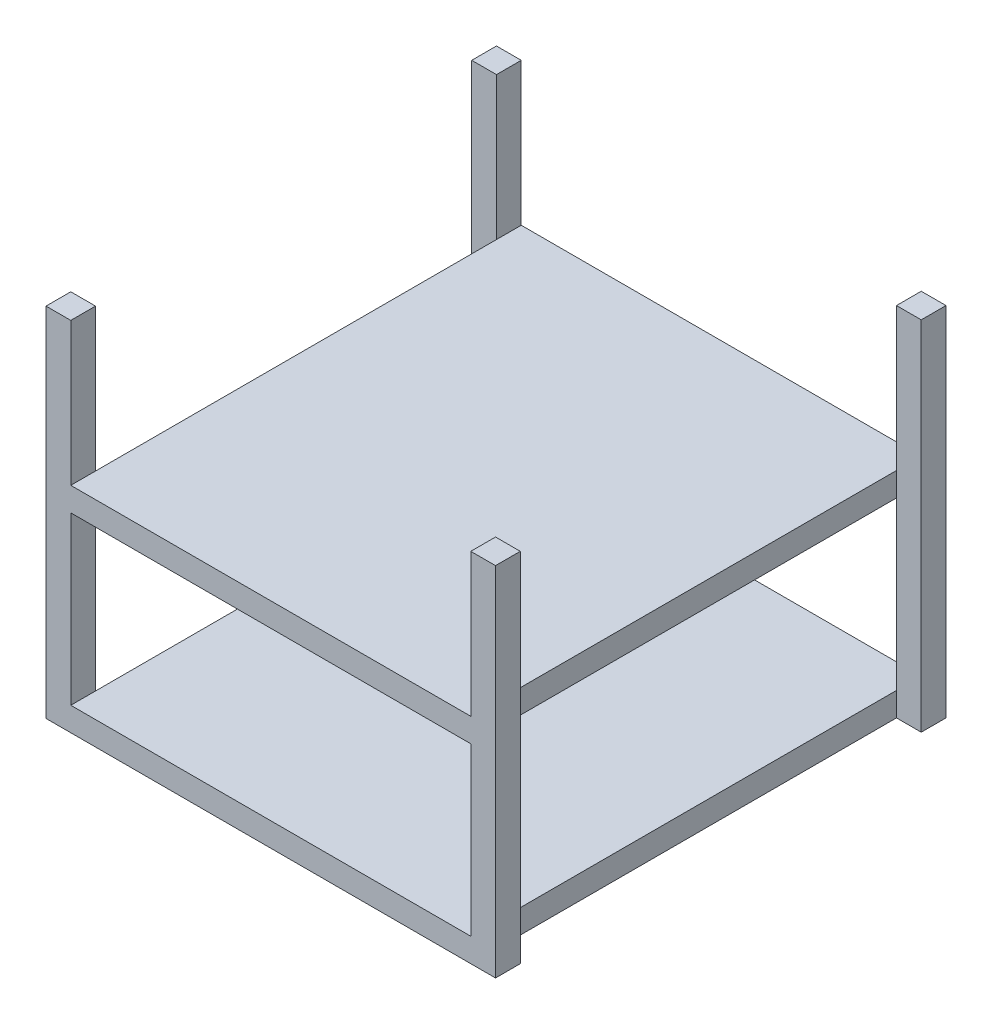
SolidWorks part; units mm, degrees
ref_plane "Front Plane" through (0, 0, 0) normal (0, 0, 1) x (1, 0, 0)
ref_plane "Top Plane" through (0, 0, 0) normal (0, 1, 0) x (1, 0, 0)
ref_plane "Right Plane" through (0, 0, 0) normal (1, 0, 0) x (0, 0, -1)
sketch "Sketch1" plane through (0, 0, 0) normal (0, 1, 0) x (1, 0, 0)
  line L0 (0, 120.142) -> (0, -120.142)
  line L1 (-127, -127) -> (127, -127)
  line L2 (-127, -127) -> (-127, 127)
  line L3 (-127, 127) -> (127, 127)
  line L4 (127, -127) -> (127, 127)
  line L5 (-127, -127) -> (127, 127) construction
  line L6 (-127, 127) -> (127, -127) construction
  line L7 (106.68, 120.142) -> (-106.68, 120.142)
  line L8 (106.68, 120.142) -> (106.68, -120.142)
  line L9 (106.68, -120.142) -> (-106.68, -120.142)
  line L10 (-106.68, 120.142) -> (-106.68, -120.142)
  line L11 (-106.68, 120.142) -> (-119.888, 120.142)
  line L12 (-106.68, 120.142) -> (-106.68, 106.934)
  line L13 (-106.68, 106.934) -> (-119.888, 106.934)
  line L14 (-119.888, 120.142) -> (-119.888, 106.934)
  line L15 (106.68, 0) -> (-106.68, 0)
  line L16 (106.68, 106.934) -> (119.888, 106.934)
  line L17 (119.888, 120.142) -> (119.888, 106.934)
  line L18 (106.68, 120.142) -> (119.888, 120.142)
  line L19 (106.68, 120.142) -> (106.68, 106.934)
  line L20 (106.68, -120.142) -> (119.888, -120.142)
  line L21 (119.888, -120.142) -> (119.888, -106.934)
  line L22 (106.68, -106.934) -> (119.888, -106.934)
  line L23 (106.68, -120.142) -> (106.68, -106.934)
  line L24 (-106.68, -106.934) -> (-119.888, -106.934)
  line L25 (-119.888, -120.142) -> (-119.888, -106.934)
  line L26 (-106.68, -120.142) -> (-119.888, -120.142)
  line L27 (-106.68, -120.142) -> (-106.68, -106.934)
  point P0 (0, 0)
  dimension "D1" = 254
  dimension "D2" = 254
  dimension "D3" = 6.858
  dimension "D4" = 6.858
  dimension "D5" = 20.32
  dimension "D6" = 20.32
  dimension "D7" = 13.208
  dimension "D8" = 13.208
extrude "Boss-Extrude1" add sketch "Sketch1" along normal blind 190.5 contours L15 L8 L7 L0 | L18 L8 L16 L17 | L8 L15 L0 L9 | L0 L15 L10 L9 | L26 L10 L24 L25 | L15 L0 L7 L10 | L12 L13 L14 L11 | L23 L22 L21 L20
sketch "Sketch3" plane through (0, 0, 120.142) normal (0, 0, 1) x (1, 0, 0)
  line L0 (119.888, 190.5) -> (-119.888, 190.5) construction
  line L1 (-106.68, 12.7) -> (106.68, 12.7)
  line L2 (-106.68, 12.7) -> (-106.68, 190.5)
  line L3 (-106.68, 190.5) -> (106.68, 190.5)
  line L4 (106.68, 12.7) -> (106.68, 190.5)
  line L5 (-119.888, 190.5) -> (-119.888, 0) construction
  line L6 (119.888, 190.5) -> (119.888, 0) construction
  line L7 (106.68, 0) -> (-106.68, 0) construction
  line L8 (-106.68, 101.6) -> (106.68, 101.6)
  line L9 (106.68, 101.6) -> (106.68, 114.3)
  line L10 (106.68, 114.3) -> (-106.68, 114.3)
  line L11 (-106.68, 114.3) -> (-106.68, 101.6)
  line M7 (119.888, 190.5) -> (-119.888, 190.5)
  dimension "D1" = 13.208
  dimension "D2" = 13.208
  dimension "D3" = 12.7
  dimension "D4" = 12.7
extrude "Cut-Extrude2" cut sketch "Sketch3" against normal blind 304.8 contours L8 L2 L1 L4 | L10 L4 L2 M7
